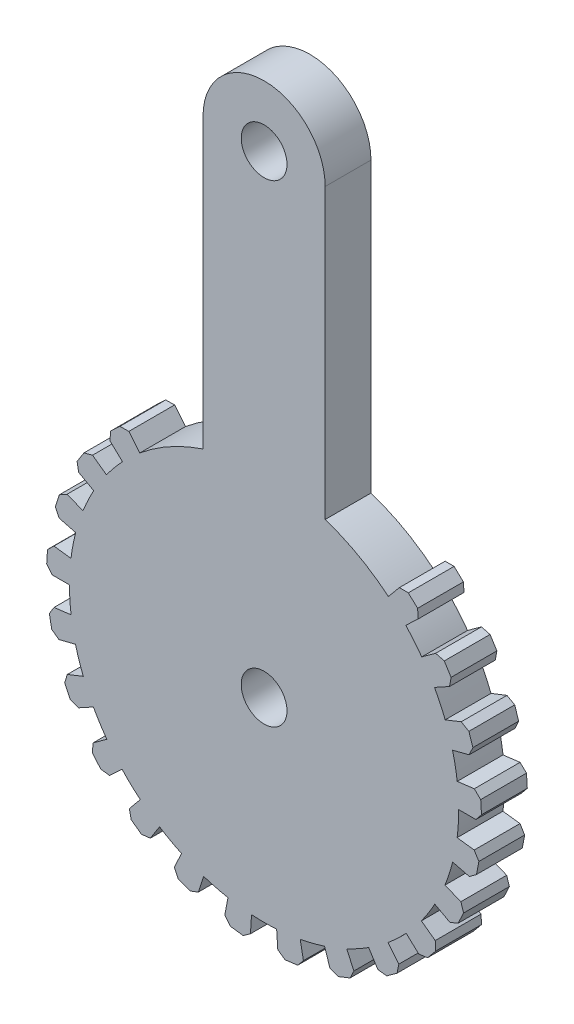
SolidWorks part; units mm, degrees
ref_plane "Front Plane" through (0, 0, 0) normal (0, 0, 1) x (1, 0, 0)
ref_plane "Top Plane" through (0, 0, 0) normal (0, 1, 0) x (1, 0, 0)
ref_plane "Right Plane" through (0, 0, 0) normal (1, 0, 0) x (0, 0, -1)
sketch "Sketch1" plane through (0, 0, 0) normal (0, 0, 1) x (1, 0, 0)
  line L5 (0, 29.5) -> (0, 31) construction
  line L9 (-6.862, 12.482) -> (-6.865, 12.4874) construction
  line L10 (-4, 12.1063) -> (-4, 31)
  line L11 (-9.7506, 10.3833) -> (-9.7548, 10.3878) construction
  line L12 (-12.0265, 7.6322) -> (-12.0317, 7.6355) construction
  line L13 (-13.5467, 4.4016) -> (-13.5526, 4.4035) construction
  line L14 (-14.2157, 0.8944) -> (-14.2219, 0.8948) construction
  line L22 (8.1443, 9.8098) -> (8.8629, 10.6754)
  line L23 (10.0978, 9.5157) -> (10.0557, 10.0968)
  line L24 (8.8629, 10.6754) -> (9.4455, 10.6698)
  line L25 (9.2791, 8.7442) -> (10.0978, 9.5157)
  line L26 (9.4455, 10.6698) -> (10.0557, 10.0968)
  line L28 (10.328, 7.4762) -> (11.2393, 8.1359)
  line L29 (12.1471, 6.7055) -> (12.2507, 7.2789)
  line L30 (11.2393, 8.1359) -> (11.8022, 7.9856)
  line L31 (11.1622, 6.1619) -> (12.1471, 6.7055)
  line L32 (11.8022, 7.9856) -> (12.2507, 7.2789)
  line L34 (11.8628, 4.6729) -> (12.9095, 5.0852)
  line L35 (13.433, 3.474) -> (13.676, 4.0036)
  line L36 (12.9095, 5.0852) -> (13.4174, 4.7996)
  line L37 (12.3439, 3.1923) -> (13.433, 3.474)
  line L38 (13.4174, 4.7996) -> (13.676, 4.0036)
  line L40 (12.6522, 1.5759) -> (13.7686, 1.715)
  line L41 (13.875, 0.0242) -> (14.242, 0.4767)
  line L42 (13.7686, 1.715) -> (14.1895, 1.312)
  line L43 (12.75, 0.0223) -> (13.875, 0.0242)
  line L44 (14.1895, 1.312) -> (14.242, 0.4767)
  line L46 (12.6467, -1.6201) -> (13.7625, -1.763)
  line L47 (13.4451, -3.4271) -> (13.9131, -3.0801)
  line L48 (13.7625, -1.763) -> (14.07, -2.258)
  line L49 (12.355, -3.1492) -> (13.4451, -3.4271)
  line L50 (14.07, -2.258) -> (13.9131, -3.0801)
  line L52 (11.8464, -4.7143) -> (12.8917, -5.1302)
  line L53 (12.1704, -6.6631) -> (12.71, -6.4434)
  line L54 (12.8917, -5.1302) -> (13.0664, -5.6861)
  line L55 (11.1836, -6.1228) -> (12.1704, -6.6631)
  line L56 (13.0664, -5.6861) -> (12.71, -6.4434)
  line L58 (10.3019, -7.5123) -> (11.2109, -8.1751)
  line L59 (10.131, -9.4804) -> (10.7083, -9.4018)
  line L60 (11.2109, -8.1751) -> (11.2418, -8.7569)
  line L61 (9.3096, -8.7117) -> (10.131, -9.4804)
  line L62 (11.2418, -8.7569) -> (10.7083, -9.4018)
  line L64 (8.11, -9.8382) -> (8.8256, -10.7063)
  line L65 (7.455, -11.7021) -> (8.0338, -11.7695)
  line L66 (8.8256, -10.7063) -> (8.7109, -11.2775)
  line L67 (6.8506, -10.7532) -> (7.455, -11.7021)
  line L68 (8.7109, -11.2775) -> (8.0338, -11.7695)
  line L70 (5.4085, -11.546) -> (5.8858, -12.5648)
  line L71 (4.3106, -13.1884) -> (4.8544, -13.3977)
  line L72 (5.8858, -12.5648) -> (5.6326, -13.0895)
  line L73 (3.9611, -12.1191) -> (4.3106, -13.1884)
  line L74 (5.6326, -13.0895) -> (4.8544, -13.3977)
  line L76 (2.3672, -12.5283) -> (2.5761, -13.6338)
  line L77 (0.8954, -13.8461) -> (1.37, -14.184)
  line L78 (2.5761, -13.6338) -> (2.2004, -14.0791)
  line L79 (0.8228, -12.7234) -> (0.8954, -13.8461)
  line L80 (2.2004, -14.0791) -> (1.37, -14.184)
  line L82 (-0.8228, -12.7234) -> (-0.8954, -13.8461)
  line L83 (-2.5761, -13.6338) -> (-2.2004, -14.0791)
  line L84 (-0.8954, -13.8461) -> (-1.37, -14.184)
  line L85 (-2.3672, -12.5283) -> (-2.5761, -13.6338)
  line L86 (-1.37, -14.184) -> (-2.2004, -14.0791)
  line L88 (-3.9611, -12.1191) -> (-4.3106, -13.1884)
  line L89 (-5.8858, -12.5648) -> (-5.6326, -13.0895)
  line L90 (-4.3106, -13.1884) -> (-4.8544, -13.3977)
  line L91 (-5.4085, -11.546) -> (-5.8858, -12.5648)
  line L92 (-4.8544, -13.3977) -> (-5.6326, -13.0895)
  line L94 (-6.8506, -10.7532) -> (-7.455, -11.7021)
  line L95 (-8.8256, -10.7063) -> (-8.7109, -11.2775)
  line L96 (-7.455, -11.7021) -> (-8.0338, -11.7695)
  line L97 (-8.11, -9.8382) -> (-8.8256, -10.7063)
  line L98 (-8.0338, -11.7695) -> (-8.7109, -11.2775)
  line L100 (-9.3096, -8.7117) -> (-10.131, -9.4804)
  line L101 (-11.2109, -8.1751) -> (-11.2418, -8.7569)
  line L102 (-10.131, -9.4804) -> (-10.7083, -9.4018)
  line L103 (-10.3019, -7.5123) -> (-11.2109, -8.1751)
  line L104 (-10.7083, -9.4018) -> (-11.2418, -8.7569)
  line L106 (-11.1836, -6.1228) -> (-12.1704, -6.6631)
  line L107 (-12.8917, -5.1302) -> (-13.0664, -5.6861)
  line L108 (-12.1704, -6.6631) -> (-12.71, -6.4434)
  line L109 (-11.8464, -4.7143) -> (-12.8917, -5.1302)
  line L110 (-12.71, -6.4434) -> (-13.0664, -5.6861)
  line L112 (-12.355, -3.1492) -> (-13.4451, -3.4271)
  line L113 (-13.7625, -1.763) -> (-14.07, -2.258)
  line L114 (-13.4451, -3.4271) -> (-13.9131, -3.0801)
  line L115 (-12.6467, -1.6201) -> (-13.7625, -1.763)
  line L116 (-13.9131, -3.0801) -> (-14.07, -2.258)
  line L118 (-12.75, 0.0223) -> (-13.875, 0.0242)
  line L119 (-13.7686, 1.715) -> (-14.1895, 1.312)
  line L120 (-13.875, 0.0242) -> (-14.242, 0.4767)
  line L121 (-12.6522, 1.5759) -> (-13.7686, 1.715)
  line L122 (-14.242, 0.4767) -> (-14.1895, 1.312)
  line L124 (-12.3439, 3.1923) -> (-13.433, 3.474)
  line L125 (-12.9095, 5.0852) -> (-13.4174, 4.7996)
  line L126 (-13.433, 3.474) -> (-13.676, 4.0036)
  line L127 (-11.8628, 4.6729) -> (-12.9095, 5.0852)
  line L128 (-13.676, 4.0036) -> (-13.4174, 4.7996)
  line L130 (-11.1622, 6.1619) -> (-12.1471, 6.7055)
  line L131 (-11.2393, 8.1359) -> (-11.8022, 7.9856)
  line L132 (-12.1471, 6.7055) -> (-12.2507, 7.2789)
  line L133 (-10.328, 7.4762) -> (-11.2393, 8.1359)
  line L134 (-12.2507, 7.2789) -> (-11.8022, 7.9856)
  line L136 (-9.2791, 8.7442) -> (-10.0978, 9.5157)
  line L137 (-8.8629, 10.6754) -> (-9.4455, 10.6698)
  line L138 (-10.0978, 9.5157) -> (-10.0557, 10.0968)
  line L139 (-8.1443, 9.8098) -> (-8.8629, 10.6754)
  line L140 (-10.0557, 10.0968) -> (-9.4455, 10.6698)
  line L148 (-13.9916, -2.669) -> (-13.9976, -2.6702) construction
  line L149 (-12.8882, -6.0647) -> (-12.8938, -6.0674) construction
  line L150 (-10.9751, -9.0794) -> (-10.9798, -9.0833) construction
  line L174 (4, 12.1063) -> (4, 31)
  circle A10 centre (0, 0) radius 1.5
  arc A11 (-4, 12.1063) -> (-5.4488, 11.5271) centre (0, 0) ccw
  arc A14 (4, 31) -> (-4, 31) centre (0, 31) ccw
  circle A15 centre (0, 31) radius 1.5
  arc A17 (8.1443, 9.8098) -> (6.813, 10.7771) centre (0, 0) ccw
  arc A18 (-0.8228, -12.7234) -> (0.8228, -12.7234) centre (0, 0) ccw
  arc A19 (-3.9611, -12.1191) -> (-2.3672, -12.5283) centre (0, 0) ccw
  arc A20 (10.328, 7.4762) -> (9.2791, 8.7442) centre (0, 0) ccw
  arc A21 (8.1443, 9.8098) -> (4, 12.1063) centre (0, 0) ccw
  arc A22 (11.8628, 4.6729) -> (11.1622, 6.1619) centre (0, 0) ccw
  arc A24 (12.6522, 1.5759) -> (12.3439, 3.1923) centre (0, 0) ccw
  arc A25 (8.1443, 9.8098) -> (4, 12.1063) centre (0, 0) ccw
  arc A26 (12.6467, -1.6201) -> (12.75, 0.0223) centre (0, 0) ccw
  arc A27 (-4, 12.1063) -> (-8.1443, 9.8098) centre (0, 0) ccw
  arc A29 (11.8464, -4.7143) -> (12.355, -3.1492) centre (0, 0) ccw
  arc A30 (5.4488, 11.5271) -> (4, 12.1063) centre (0, 0) ccw
  arc A31 (10.3019, -7.5123) -> (11.1836, -6.1228) centre (0, 0) ccw
  arc A32 (-9.4455, 10.6698) -> (-10.0557, 10.0968) centre (0, 0) ccw
  arc A33 (-11.8022, 7.9856) -> (-12.2507, 7.2789) centre (0, 0) ccw
  arc A34 (-13.4174, 4.7996) -> (-13.676, 4.0036) centre (0, 0) ccw
  arc A35 (-14.1895, 1.312) -> (-14.242, 0.4767) centre (0, 0) ccw
  arc A36 (-14.07, -2.258) -> (-13.9131, -3.0801) centre (0, 0) ccw
  arc A37 (-13.0664, -5.6861) -> (-12.71, -6.4434) centre (0, 0) ccw
  arc A38 (-10.9798, -9.0833) -> (-10.7083, -9.4018) centre (0, 0) ccw
  arc A45 (8.1443, 9.8098) -> (6.813, 10.7771) centre (0, 0) ccw
  arc A46 (8.11, -9.8382) -> (9.3096, -8.7117) centre (0, 0) ccw
  arc A47 (5.4085, -11.546) -> (6.8506, -10.7532) centre (0, 0) ccw
  arc A48 (2.3672, -12.5283) -> (3.9611, -12.1191) centre (0, 0) ccw
  arc A49 (-0.8228, -12.7234) -> (0.8228, -12.7234) centre (0, 0) ccw
  arc A50 (-6.8506, -10.7532) -> (-5.4085, -11.546) centre (0, 0) ccw
  arc A51 (-9.3096, -8.7117) -> (-8.11, -9.8382) centre (0, 0) ccw
  arc A52 (-11.1836, -6.1228) -> (-10.3019, -7.5123) centre (0, 0) ccw
  arc A53 (-12.355, -3.1492) -> (-11.8464, -4.7143) centre (0, 0) ccw
  arc A54 (-12.75, 0.0223) -> (-12.6467, -1.6201) centre (0, 0) ccw
  arc A55 (-12.3439, 3.1923) -> (-12.6522, 1.5759) centre (0, 0) ccw
  arc A56 (-11.1622, 6.1619) -> (-11.8628, 4.6729) centre (0, 0) ccw
  arc A57 (-9.2791, 8.7442) -> (-10.328, 7.4762) centre (0, 0) ccw
  arc A58 (-6.813, 10.7771) -> (-8.1443, 9.8098) centre (0, 0) ccw
  point P4 (0, 15.5)
  point P183 (0, 0)
  dimension "D1" = 3
  dimension "D2" = 25.5
  dimension "D8" = 31
extrude "Boss-Extrude2" add sketch "Sketch1" along normal blind 3
